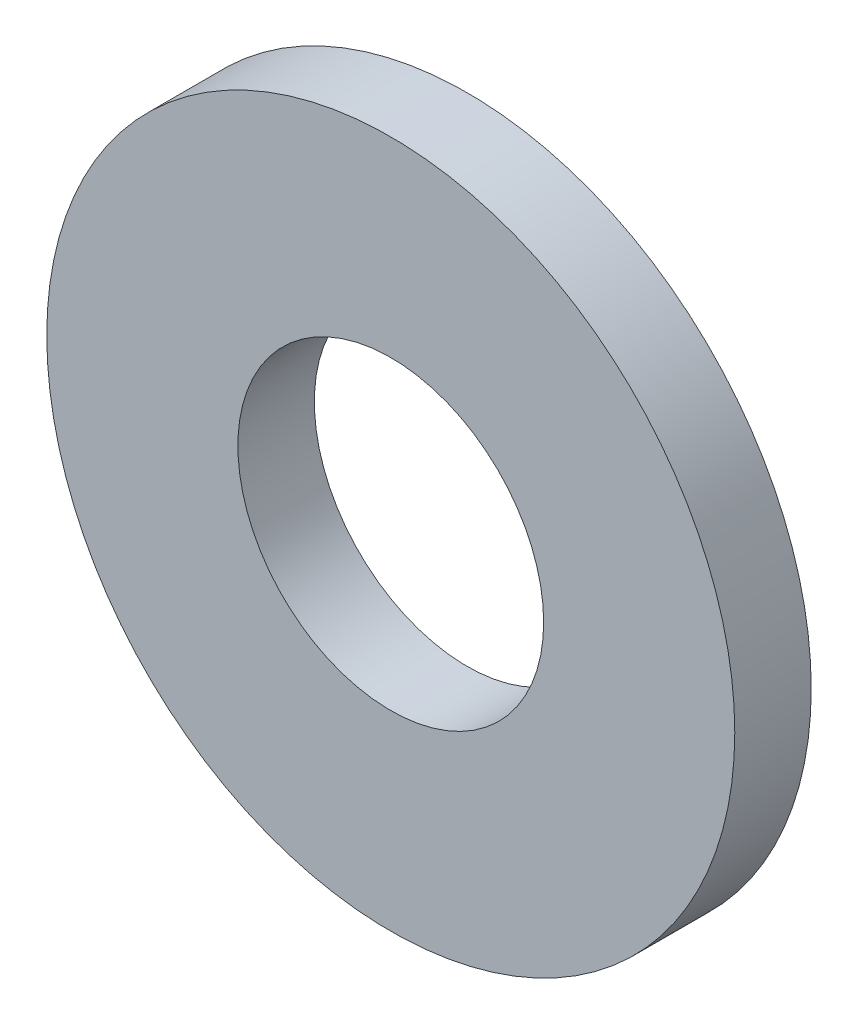
SolidWorks part; units mm, degrees
ref_plane "前视基准面" through (0, 0, 0) normal (0, 0, 1) x (1, 0, 0)
ref_plane "上视基准面" through (0, 0, 0) normal (0, 1, 0) x (1, 0, 0)
ref_plane "右视基准面" through (0, 0, 0) normal (1, 0, 0) x (0, 0, -1)
sketch "草图1" plane through (0, 0, 0) normal (0, 0, 1) x (1, 0, 0)
  circle A0 centre (0, 0) radius 2
  circle A1 centre (0, 0) radius 4.5
extrude "凸台-拉伸1" add sketch "草图1" along normal blind 1
